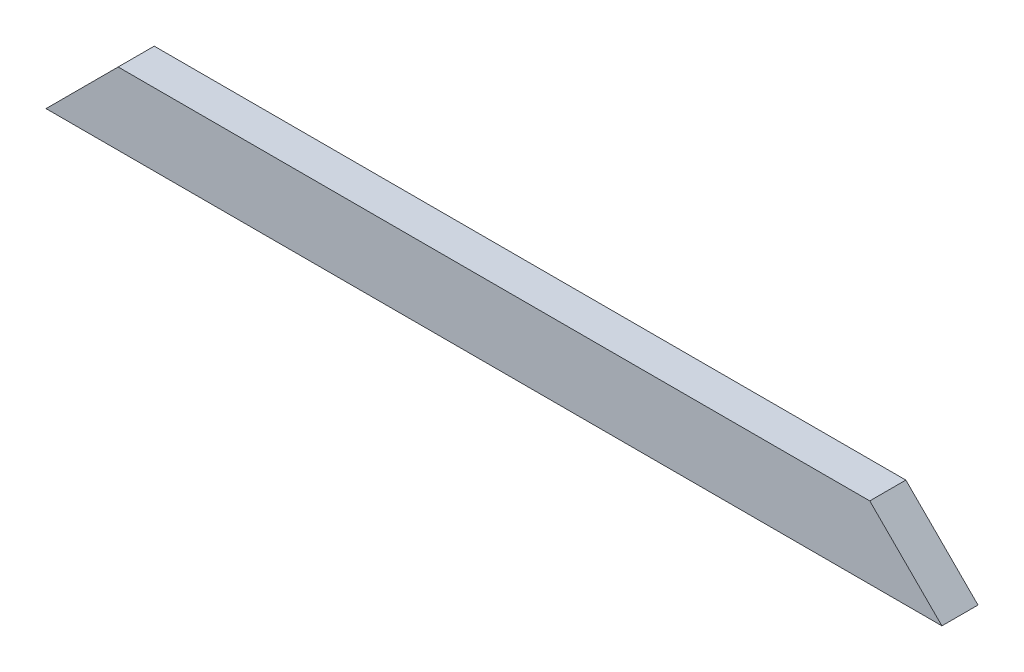
SolidWorks part; units mm, degrees
ref_plane "Front Plane" through (0, 0, 0) normal (0, 0, 1) x (1, 0, 0)
ref_plane "Top Plane" through (0, 0, 0) normal (0, 1, 0) x (1, 0, 0)
ref_plane "Right Plane" through (0, 0, 0) normal (1, 0, 0) x (0, 0, -1)
sketch "Sketch1" plane through (0, 0, 0) normal (0, 0, 1) x (1, 0, 0)
  line L0 (0, 0) -> (38.1, 38.1)
  line L1 (0, 0) -> (473.075, 0)
  line L3 (38.1, 38.1) -> (434.975, 38.1)
  line L5 (473.075, 0) -> (434.975, 38.1)
  dimension "D1" = 38.1
  dimension "D2" = 473.075
  dimension "D3" = 45
  dimension "D4" = 45
extrude "Boss-Extrude1" add sketch "Sketch1" along normal blind 19.05
